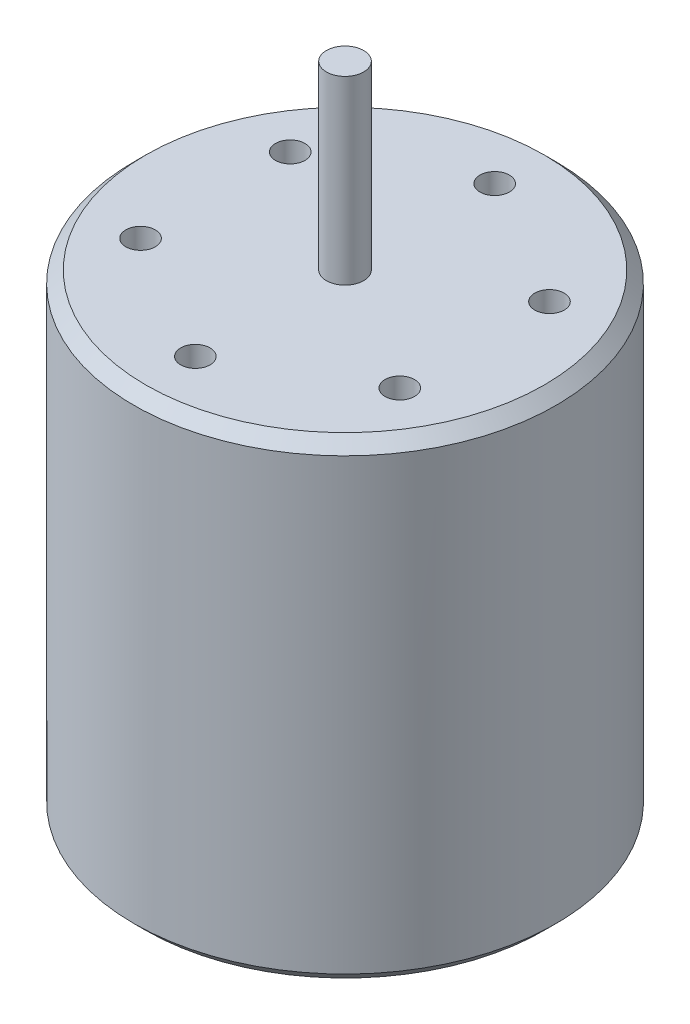
SolidWorks part; units mm, degrees
ref_plane "Front Plane" through (0, 0, 0) normal (0, 0, 1) x (1, 0, 0)
ref_plane "Top Plane" through (0, 0, 0) normal (0, 1, 0) x (1, 0, 0)
ref_plane "Right Plane" through (0, 0, 0) normal (1, 0, 0) x (0, 0, -1)
sketch "Sketch1" plane through (0, 0, 0) normal (0, 1, 0) x (1, 0, 0)
  circle A0 centre (0, 0) radius 17.907
  dimension "D1" = 35.814
extrude "Boss-Extrude1" add sketch "Sketch1" along normal blind 40.0812
hole_wizard "M3x0.5 Bottoming Tapped Hole1" positions "Sketch3" profile "Sketch2" tap size "M3x0.5" standard "HASCO Metric"
sketch "Sketch3" plane through (0, 40.0812, 0) normal (0, 1, 0) x (1, 0, 0)
  point P2 (0, 12.7)
  point P11 (10.9985, 6.35)
  point P12 (10.9985, -6.35)
  point P13 (0, -12.7)
  point P14 (-10.9985, -6.35)
  point P15 (-10.9985, 6.35)
  dimension "D2" = 6
sketch "Sketch2" plane through (0, 40.0812, -12.7) normal (1, 0, 0) x (0, 0, 1)
  line L0 (0, 0) -> (0, 5.7511)
  line L1 (0, 5.7511) -> (1.25, 5)
  line L2 (1.25, 5) -> (1.25, 0)
  line L5 (1.25, 0) -> (0, 0)
  line L10 (0, 5.7511) -> (-1.25, 5) construction
  line L11 (0, -6.35) -> (0, 107.95) construction
  dimension "Tap Drill Dia." = 2.5
  dimension "Tap Drill Depth" = 5
  dimension "Drill Angle" = 118
sketch "Sketch4" plane through (0, 40.0812, 0) normal (0, 1, 0) x (1, 0, 0)
  circle A0 centre (0, 0) radius 1.58
  dimension "D1" = 3.16
extrude "Boss-Extrude2" add sketch "Sketch4" along normal blind 15.3416
chamfer "Chamfer1" distance 1 angle 45 2 edges at (0, 40.0812, 17.907) (0, 0, 17.907)
